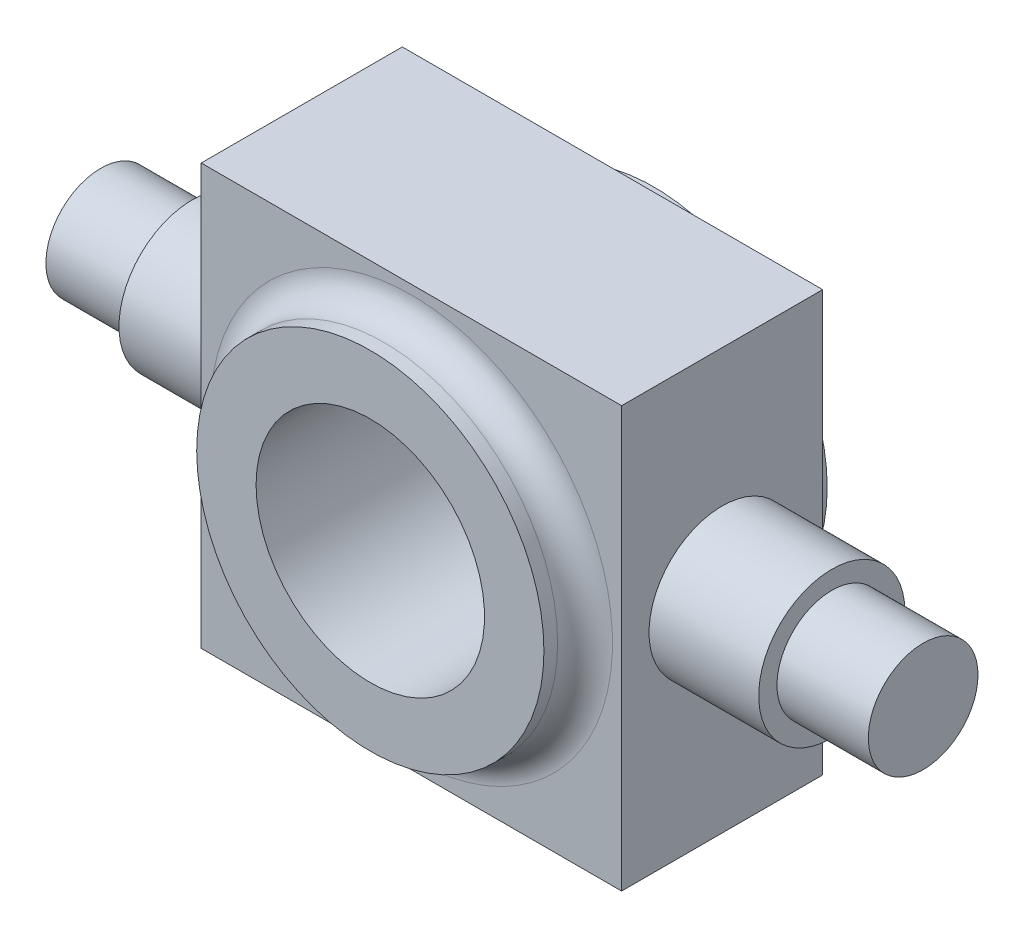
SolidWorks part; units mm, degrees
ref_plane "Front Plane" through (0, 0, 0) normal (0, 0, 1) x (1, 0, 0)
ref_plane "Top Plane" through (0, 0, 0) normal (0, 1, 0) x (1, 0, 0)
ref_plane "Right Plane" through (0, 0, 0) normal (1, 0, 0) x (0, 0, -1)
sketch "Sketch1" plane through (0, 0, 0) normal (0, 1, 0) x (1, 0, 0)
  line L1 (-23, 11) -> (23, 11)
  line L2 (-23, 11) -> (-23, -11)
  line L3 (-23, -11) -> (23, -11)
  line L4 (23, 11) -> (23, -11)
  line L5 (-23, 11) -> (23, -11) construction
  line L6 (-23, -11) -> (23, 11) construction
  point P0 (0, 0)
  dimension "D1" = 22
  dimension "D2" = 46
extrude "Boss-Extrude1" add sketch "Sketch1" along normal mid plane 46
sketch "Sketch2" plane through (0, 0, 11) normal (0, 0, 1) x (1, 0, 0)
  circle A0 centre (0, 0) radius 19
  dimension "D1" = 38
extrude "Boss-Extrude2" add sketch "Sketch2" along normal blind 4.5 and the other way blind 26.5
sketch "Sketch3" plane through (0, 0, 0) normal (0, 1, 0) x (1, 0, 0)
  line L0 (0, 15.5) -> (0, -15.5)
  line L1 (19, 15.5) -> (-19, 15.5) construction
  line L2 (-19, -15.5) -> (19, -15.5) construction
  line L3 (0, -15.5) -> (12.5, -15.5)
  line L4 (12.5, -15.5) -> (12.5, 12.5)
  line L5 (12.5, 12.5) -> (16, 12.5)
  line L6 (16, 12.5) -> (16, 15.5)
  line L7 (16, 15.5) -> (0, 15.5)
  dimension "D1" = 12.5
  dimension "D2" = 3
  dimension "D3" = 16
revolve "Cut-Revolve1" cut sketch "Sketch3" angle 360 about L0
sketch "Sketch4" plane through (0, 0, 0) normal (0, 1, 0) x (1, 0, 0)
  line L0 (-23, 0) -> (-45, 0) construction
  line L1 (-23, 11) -> (-23, -11) construction
  line L2 (-45, 0) -> (-45, 6)
  line L3 (-45, 6) -> (-35, 6)
  line L4 (-35, 6) -> (-35, 8)
  line L5 (-35, 8) -> (-23, 8)
  line L6 (-23, 8) -> (-23, 0)
  line L7 (-23, 0) -> (-45, 0)
  dimension "D1" = 16
  dimension "D2" = 12
  dimension "D3" = 12
  dimension "D4" = 10
revolve "Revolve1" add sketch "Sketch4" angle 360 about L0
mirror "Mirror1" about plane through (0, 0, 0) normal (1, 0, 0) of "Revolve1"
fillet "Fillet1" radius 3 2 edges at (-19, 0, 11) (19, 0, -11)
